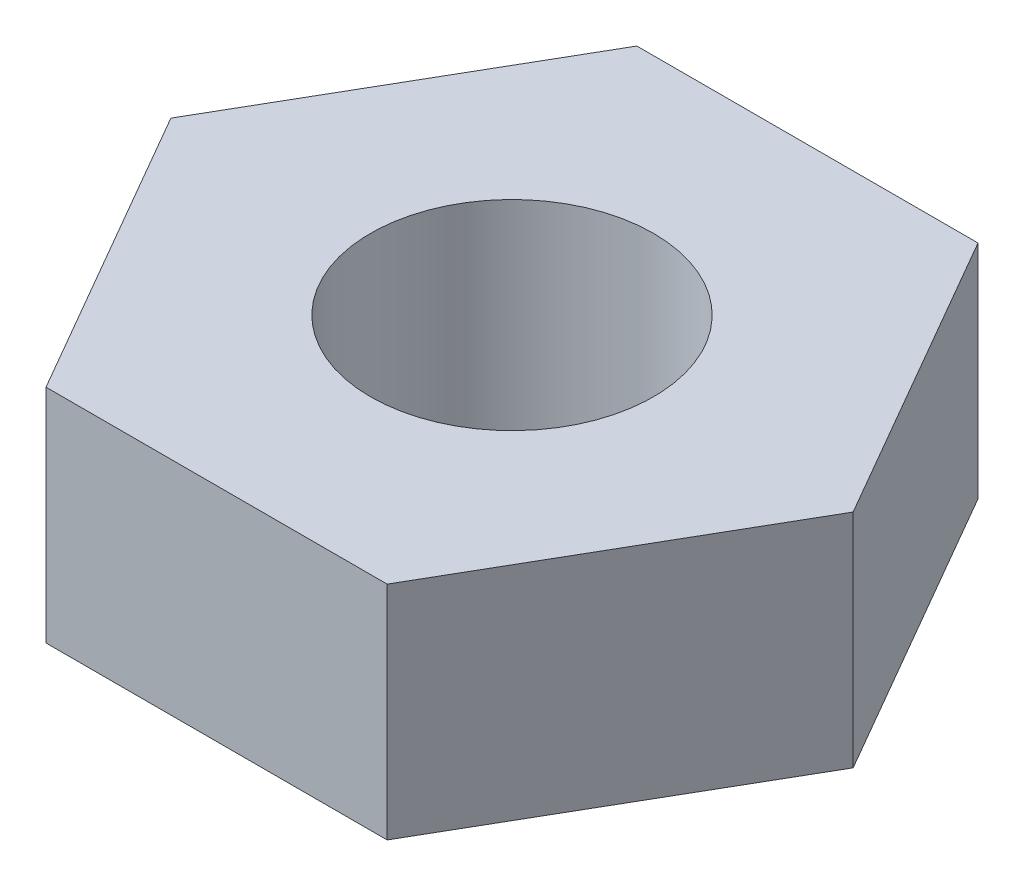
SolidWorks part; units mm, degrees
ref_plane "前视基准面" through (0, 0, 0) normal (0, 0, 1) x (1, 0, 0)
ref_plane "上视基准面" through (0, 0, 0) normal (0, 1, 0) x (1, 0, 0)
ref_plane "右视基准面" through (0, 0, 0) normal (1, 0, 0) x (0, 0, -1)
other "Configuration Table"
sketch "草图1" plane through (0, 0, 0) normal (0, 1, 0) x (1, 0, 0)
  line L1 (2.7713, 0) -> (1.3856, 2.4)
  line L2 (1.3856, 2.4) -> (-1.3856, 2.4)
  line L3 (-1.3856, 2.4) -> (-2.7713, 0)
  line L4 (-2.7713, 0) -> (-1.3856, -2.4)
  line L5 (-1.3856, -2.4) -> (1.3856, -2.4)
  line L6 (1.3856, -2.4) -> (2.7713, 0)
  circle A0 centre (0, 0) radius 2.4 construction
  circle A1 centre (0, 0) radius 1.15
  dimension "D1" = 4.8
  dimension "D2" = 2.3
extrude "凸台-拉伸1" add sketch "草图1" along normal blind 1.8
